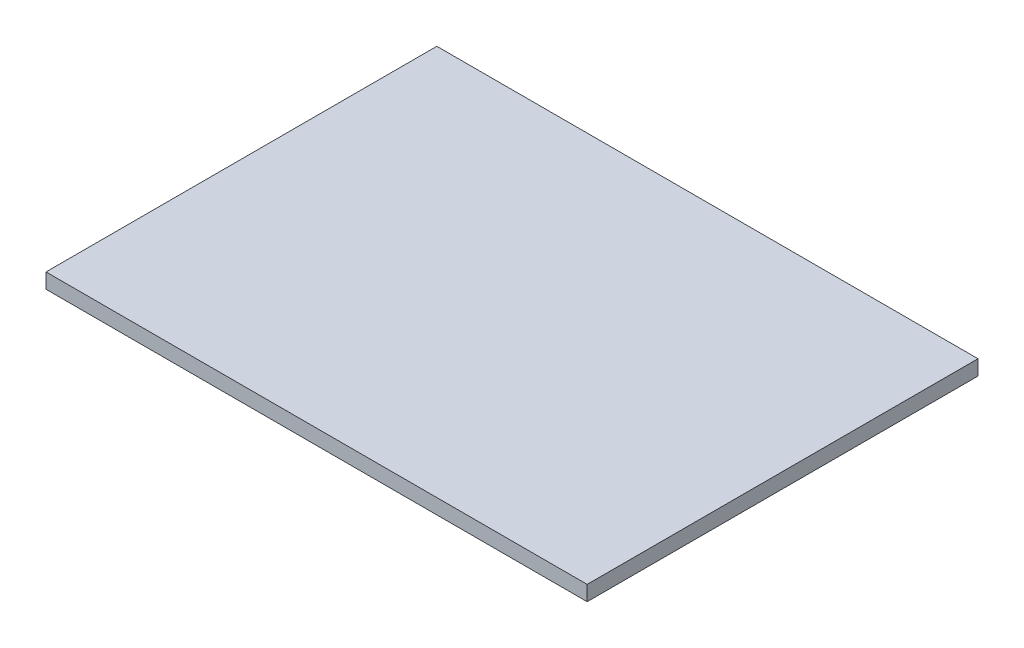
SolidWorks part; units mm, degrees
ref_plane "Front Plane" through (0, 0, 0) normal (0, 0, 1) x (1, 0, 0)
ref_plane "Top Plane" through (0, 0, 0) normal (0, 1, 0) x (1, 0, 0)
ref_plane "Right Plane" through (0, 0, 0) normal (1, 0, 0) x (0, 0, -1)
sketch "Sketch2" plane through (0, 0, 0) normal (0, 1, 0) x (1, 0, 0)
  line L1 (0, 0) -> (180, 0)
  line L2 (0, 0) -> (0, -130)
  line L3 (0, -130) -> (180, -130)
  line L4 (180, 0) -> (180, -130)
  dimension "D1" = 130
  dimension "D2" = 180
extrude "Boss-Extrude1" add sketch "Sketch2" along normal blind 5
